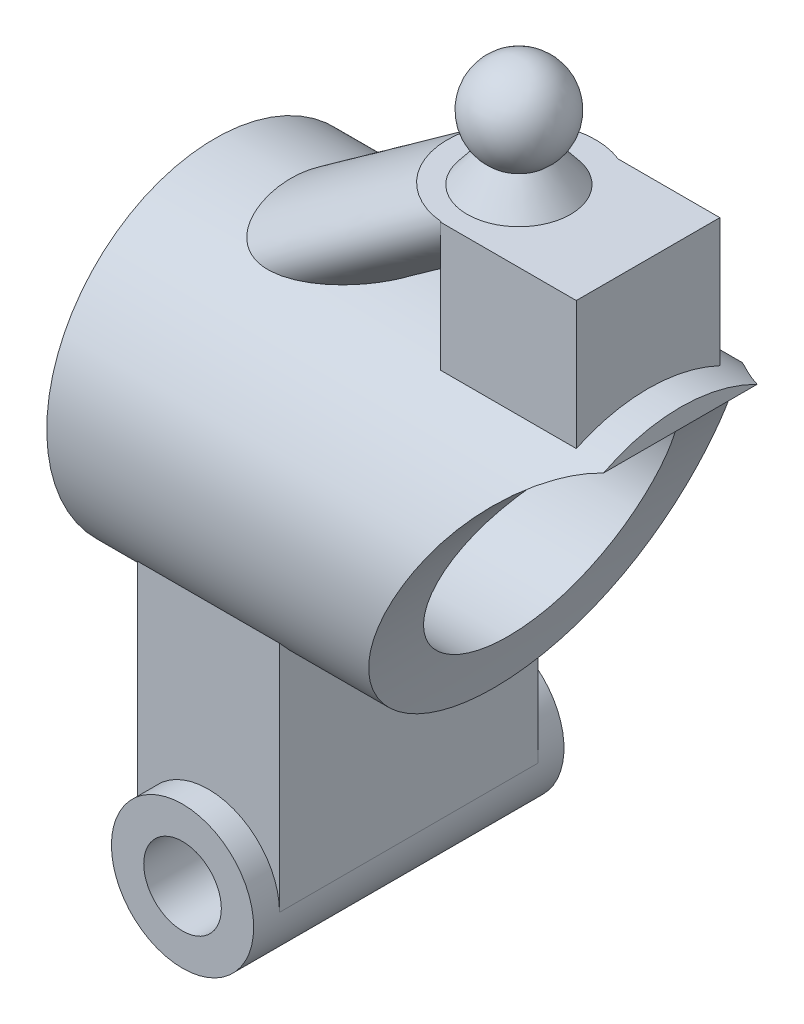
SolidWorks part; units mm, degrees
ref_plane "前视基准面" through (0, 0, 0) normal (0, 0, 1) x (1, 0, 0)
ref_plane "上视基准面" through (0, 0, 0) normal (0, 1, 0) x (1, 0, 0)
ref_plane "右视基准面" through (0, 0, 0) normal (1, 0, 0) x (0, 0, -1)
sketch "草图1" plane through (0, 0, 0) normal (0, 0, 1) x (1, 0, 0)
  line L0 (-2.75, 0) -> (-2.75, 9.5)
  line L1 (-2.75, 9.5) -> (2.75, 9.5)
  line L2 (2.75, 9.5) -> (2.75, 0)
  circle A0 centre (0, 0) radius 1.5
  arc A1 (-2.75, 0) -> (2.75, 0) centre (0, 0) ccw
extrude "凸台-拉伸1" add sketch "草图1" along normal blind 10
sketch "草图2" plane through (0, 0, 0) normal (0, 0, -1) x (-1, 0, 0)
  circle A0 centre (0, 0) radius 1.5
  circle A1 centre (0, 0) radius 2.75
extrude "凸台-拉伸2" add sketch "草图2" along normal blind 1
sketch "草图3" plane through (0, 0, 10) normal (0, 0, 1) x (1, 0, 0)
  circle A0 centre (0, 0) radius 1.5
  circle A1 centre (0, 0) radius 2.75
  dimension "D1" = 5.5
extrude "凸台-拉伸3" add sketch "草图3" along normal blind 1
ref_plane "基准面1" through (-4.75, 0, 0) normal (-1, 0, 0) x (0, 0, 1)
sketch "草图5" plane through (-4.75, 0, 0) normal (-1, 0, 0) x (0, 0, 1)
  line L0 (0, -0.3351) -> (5, -0.3351)
  line L1 (5, -0.3351) -> (5, 13.1649)
  line L2 (10, 9.5) -> (10, 0) construction
  circle A0 centre (5, 13.1649) radius 6.5
  dimension "D1" = 5
  dimension "D2" = 5
  dimension "D3" = 13.5
extrude "凸台-拉伸4" add sketch "草图5" against normal blind 18
sketch "草图7" plane through (-4.75, 0, 0) normal (-1, 0, 0) x (0, 0, 1)
  circle A0 centre (5, 13.1649) radius 4.5
  circle A1 centre (5, 13.1649) radius 6.5 construction
  dimension "D1" = 2
extrude "切除-拉伸1" cut sketch "草图7" against normal blind 18
sketch "草图8" plane through (-4.75, 0, 0) normal (-1, 0, 0) x (0, 0, 1)
  line L0 (0, 0) -> (5, 0)
  line L1 (5, 0) -> (5, 19.0425)
  line L2 (5, 19.0425) -> (2.2244, 19.0425)
  line L3 (2.2244, 19.0425) -> (7.7756, 19.0425)
  circle A2 centre (5, 13.1649) radius 6.5 construction
  dimension "D1" = 5
ref_plane "基准面2" through (0, 19, 0) normal (0, 1, 0) x (1, 0, 0)
sketch "草图9" plane through (0, 19, 0) normal (0, 1, 0) x (1, 0, 0)
  line L2 (-0.0074, -2.0155) -> (11.9926, -2.0155)
  line L3 (0, -2.0154) -> (-0.0074, -2.0155)
  line L5 (-0.0074, -7.7555) -> (12, -7.7555)
  line L6 (12, -7.7555) -> (11.9926, -2.0155)
  line L7 (33.1305, 6.8008) -> (33.1305, 6.3122)
  circle A1 centre (-0.0074, -4.8855) radius 2.87
ref_plane "基准面4" through (0, 0, 5) normal (0, 0, -1) x (-1, 0, 0)
sketch "草图11" plane through (0, 0, 5) normal (0, 0, -1) x (-1, 0, 0)
  line L3 (-7, 24) -> (0, 19)
sweep "扫描2" add profiles "草图9" path "草图11"
sketch "草图12" plane through (0, 19, 0) normal (0, 1, 0) x (1, 0, 0)
  line L0 (-4.75, -5) -> (0, -5)
  line L1 (0, -5) -> (12, -5)
  line L2 (-4.75, -2.2244) -> (12, -2.2244)
  line L3 (12, -2.2244) -> (12, -5)
  line L4 (-4.75, -7.7756) -> (12, -7.7756)
  line L5 (12, -7.7756) -> (12, -5)
  line L6 (6.7507, -2.2244) -> (6.7507, -7.7756)
extrude "凸台-拉伸5" add sketch "草图12" along normal blind 5 contours L2 L6 L1 L3 | L1 L6 L4 L5
sketch "草图13" plane through (0, 0, 5) normal (0, 0, -1) x (-1, 0, 0)
  line L0 (0, 0) -> (0, 24)
  line L1 (0, 24) -> (-7.0062, 24)
  line L2 (-7.0062, 24) -> (-5.0062, 24)
  line L3 (-7.0062, 24) -> (-7.0062, 26.5)
  line L4 (-5.0062, 24) -> (-5.913, 25.1335)
  line L5 (-7.0062, 26.5) -> (-7.0062, 28.25)
  arc A0 (-5.913, 25.1335) -> (-7.0062, 28.25) centre (-7.0062, 26.5) ccw
  dimension "D1" = 90
  dimension "D2" = 180
  dimension "D3" = 2.5
revolve "旋转1" add sketch "草图13" angle 360 about L5
sketch "草图14" plane through (0, 0, 5) normal (0, 0, -1) x (-1, 0, 0)
  line L2 (-13.5, 19) -> (-13.5, 6.5)
  line L3 (-13.5, 6.5) -> (-6, 6.5)
  spline S0 degree 3 poles (-13.5, 19) (-11.1923, 18.5688) (-8.1117, 14.1471) (-6.7531, 9.3196) (-6, 6.5) knots 0 0 0 0 0.426489 1 1 1 1
extrude "切除-拉伸2" cut sketch "草图14" against normal mid plane 40
